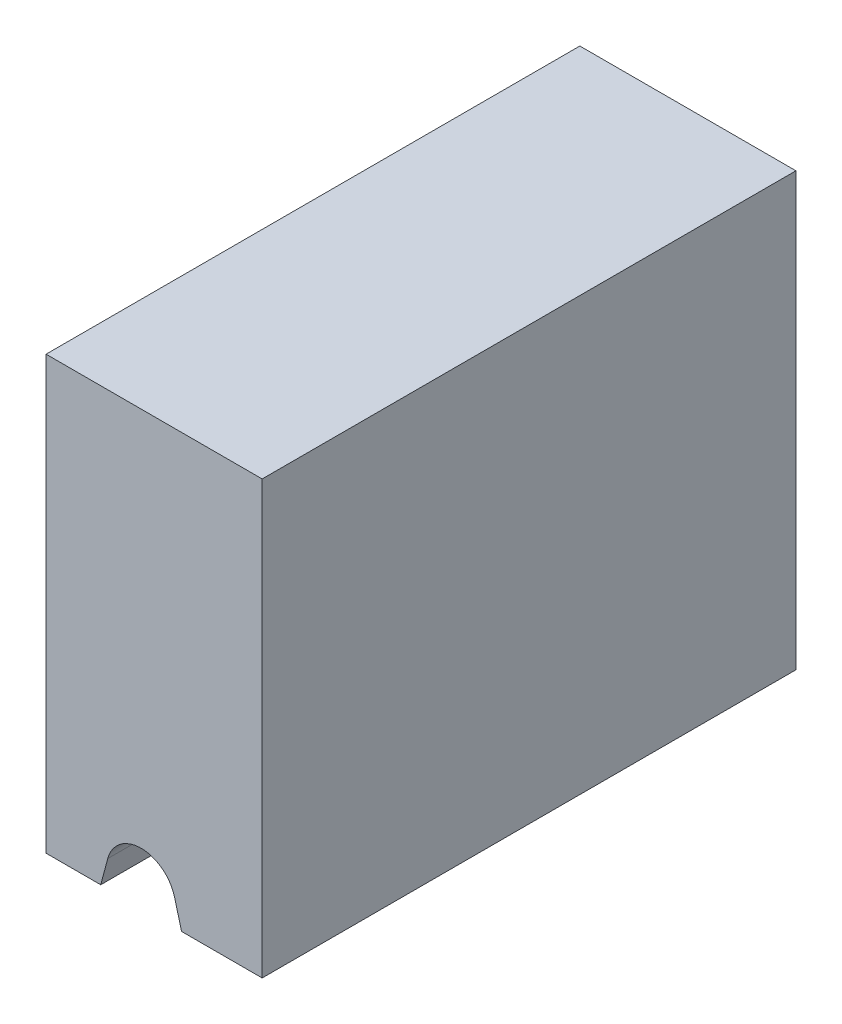
SolidWorks part; units mm, degrees
material "K110"
ref_plane "Front Plane" through (0, 0, 0) normal (0, 0, 1) x (1, 0, 0)
ref_plane "Top Plane" through (0, 0, 0) normal (0, 1, 0) x (1, 0, 0)
ref_plane "Right Plane" through (0, 0, 0) normal (1, 0, 0) x (0, 0, -1)
sketch "Sketch1" plane through (0, 0, 0) normal (0, 0, 1) x (1, 0, 0)
  line L1 (-12.5, -50) -> (12.5, -50)
  line L2 (-12.5, -50) -> (-12.5, 0)
  line L3 (-12.5, 0) -> (12.5, 0)
  line L4 (12.5, -50) -> (12.5, 0)
  point P4 (0, 0)
  dimension "D1" = 25
  dimension "D2" = 50
extrude "Boss-Extrude1" add sketch "Sketch1" along normal mid plane 61.75
sketch "Sketch2" plane through (0, 0, -30.875) normal (0, 0, -1) x (-1, 0, 0)
  line L0 (-2.3637, -46.9647) -> (-3.177, -50)
  line L1 (12.5, -50) -> (-12.5, -50) construction
  line L2 (-2.3637, -46.9647) -> (-2.3637, -50) construction
  line L3 (1.5, -48) -> (1.5, -44) construction
  line L4 (5.3637, -46.9647) -> (6.177, -50)
  line L5 (-3.177, -50) -> (6.177, -50)
  line L6 (-12.5, -50) -> (-12.5, 0) construction
  line L7 (5.3637, -46.9647) -> (5.3637, -50) construction
  arc A1 (5.3637, -46.9647) -> (-2.3637, -46.9647) centre (1.5, -48) ccw
  dimension "D2" = 4
  dimension "D1" = 15
  dimension "D3" = 2
  dimension "D4" = 14
  dimension "D5" = 15
extrude "Cut-Extrude1" cut sketch "Sketch2" against normal up to next
